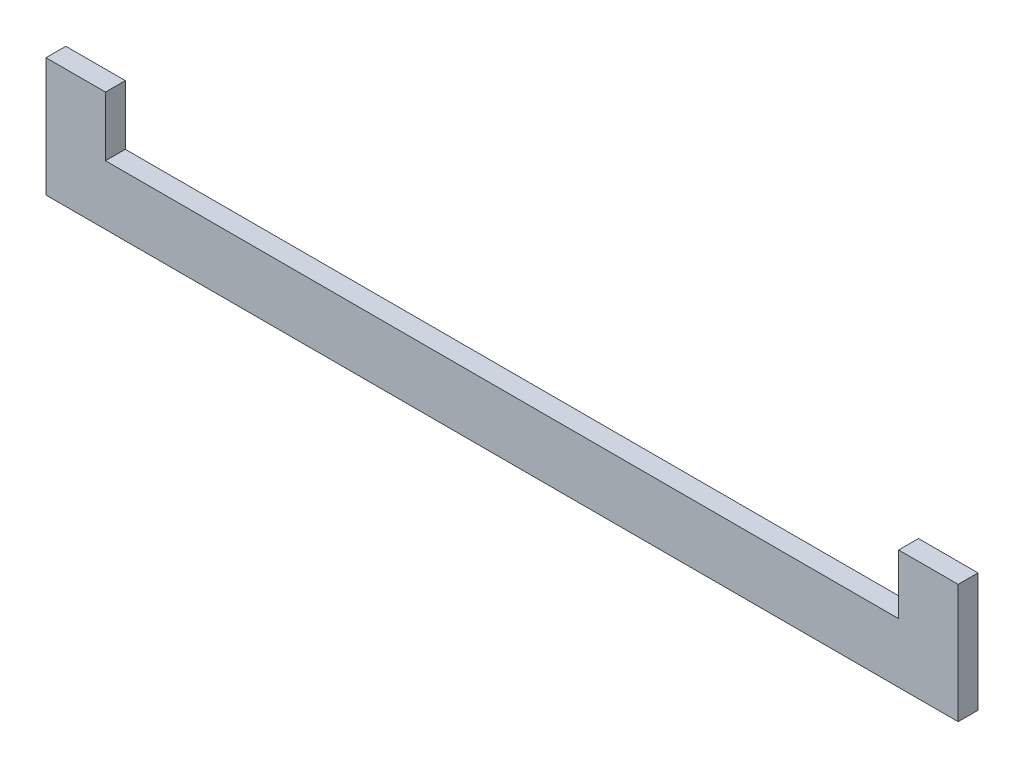
SolidWorks part; units mm, degrees
ref_plane "Alzado" through (0, 0, 0) normal (0, 0, 1) x (1, 0, 0)
ref_plane "Planta" through (0, 0, 0) normal (0, 1, 0) x (1, 0, 0)
ref_plane "Vista lateral" through (0, 0, 0) normal (1, 0, 0) x (0, 0, -1)
sketch "Croquis1" plane through (0, 0, 0) normal (0, 0, 1) x (1, 0, 0)
  line L1 (-84.8752, 50) -> (115.1248, 50)
  line L3 (-84.8752, 35) -> (115.1248, 35)
  line L5 (-84.8752, 35) -> (-99.8752, 35)
  line L6 (-84.8752, 50) -> (-84.8752, 65)
  line L7 (-84.8752, 65) -> (-99.8752, 65)
  line L8 (-99.8752, 35) -> (-99.8752, 65)
  line L9 (115.1248, 35) -> (130.1248, 35)
  line L10 (115.1248, 50) -> (115.1248, 65)
  line L11 (115.1248, 65) -> (130.1248, 65)
  line L12 (130.1248, 35) -> (130.1248, 65)
  dimension "D1" = 200
  dimension "D2" = 15
  dimension "D3" = 30
  dimension "D4" = 30
  dimension "D5" = 15
  dimension "D6" = 15
extrude "Saliente-Extruir1" add sketch "Croquis1" along normal blind 5
